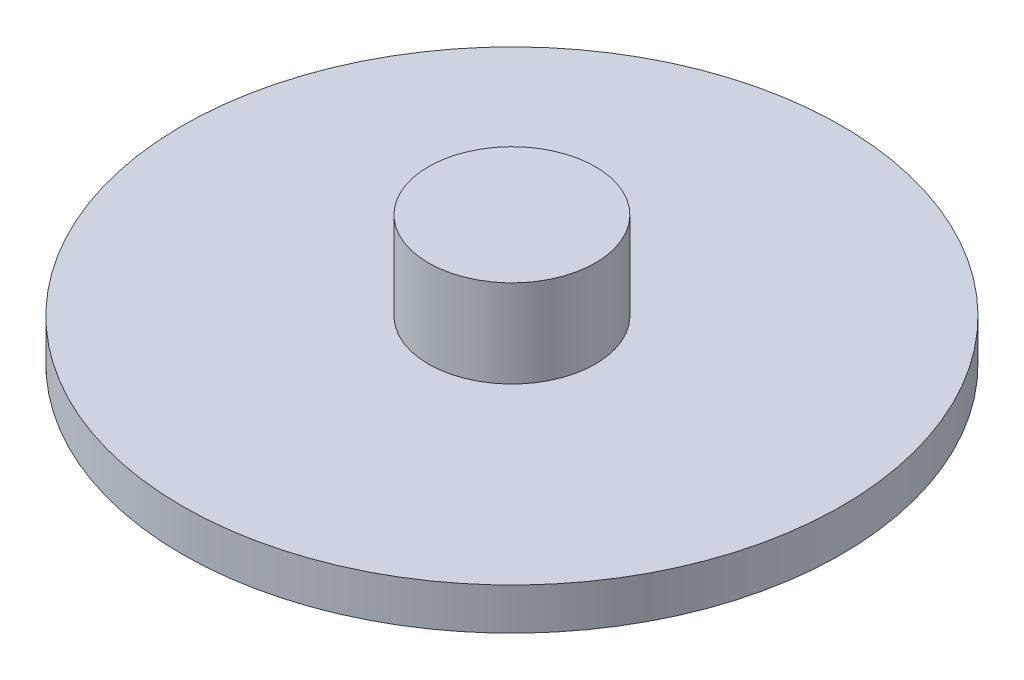
SolidWorks part; units mm, degrees
material "201 Annealed Stainless Steel (SS)"
ref_plane "Front Plane" through (0, 0, 0) normal (0, 0, 1) x (1, 0, 0)
ref_plane "Top Plane" through (0, 0, 0) normal (0, 1, 0) x (1, 0, 0)
ref_plane "Right Plane" through (0, 0, 0) normal (1, 0, 0) x (0, 0, -1)
sketch "Sketch1" plane through (0, 0, 0) normal (0, 1, 0) x (1, 0, 0)
  circle A0 centre (0, 0) radius 7.9
  dimension "D1" = 15.8
extrude "Boss-Extrude1" add sketch "Sketch1" along normal blind 1
sketch "Sketch2" plane through (0, 1, 0) normal (0, 1, 0) x (1, 0, 0)
  circle A0 centre (0, 0) radius 2
  dimension "D1" = 4
extrude "Boss-Extrude2" add sketch "Sketch2" along normal blind 2.1
